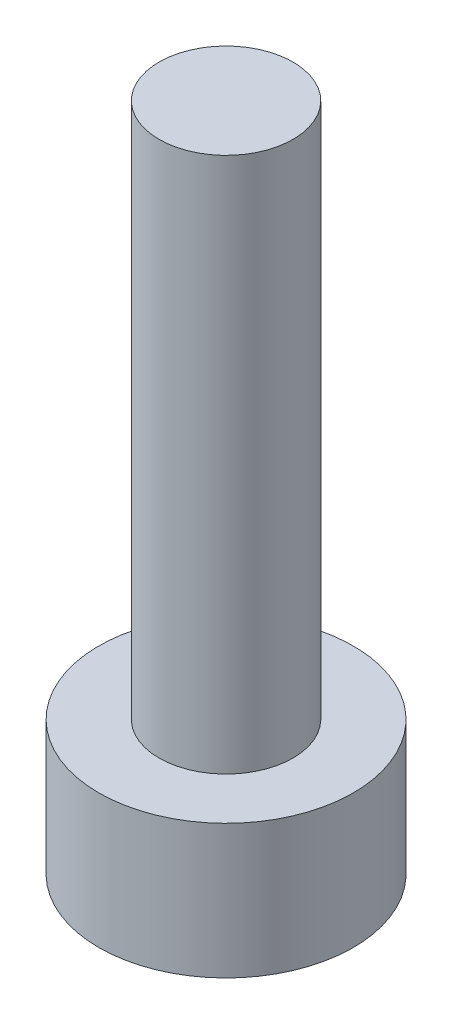
SolidWorks part; units mm, degrees
ref_plane "Ön Düzlem" through (0, 0, 0) normal (0, 0, 1) x (1, 0, 0)
ref_plane "Üst Düzlem" through (0, 0, 0) normal (0, 1, 0) x (1, 0, 0)
ref_plane "Sağ Düzlem" through (0, 0, 0) normal (1, 0, 0) x (0, 0, -1)
sketch "Sketch1" plane through (0, 0, 0) normal (0, 1, 0) x (1, 0, 0)
  circle A0 centre (0, 0) radius 1.9
  dimension "D1" = 3.8
extrude "Boss-Extrude1" add sketch "Sketch1" along normal blind 2
sketch "Sketch2" plane through (0, 2, 0) normal (0, 1, 0) x (1, 0, 0)
  circle A0 centre (0, 0) radius 1
  dimension "D1" = 2
extrude "Boss-Extrude2" add sketch "Sketch2" along normal blind 8
sketch "Sketch3" plane through (0, 0, 0) normal (0, -1, 0) x (-1, 0, 0)
  line L1 (-0.866, 0) -> (-0.433, -0.75)
  line L2 (-0.433, -0.75) -> (0.433, -0.75)
  line L3 (0.433, -0.75) -> (0.866, 0)
  line L4 (0.866, 0) -> (0.433, 0.75)
  line L5 (0.433, 0.75) -> (-0.433, 0.75)
  line L6 (-0.433, 0.75) -> (-0.866, 0)
  circle A0 centre (0, 0) radius 0.75 construction
  dimension "D1" = 1.5
extrude "Cut-Extrude1" cut sketch "Sketch3" against normal blind 1
